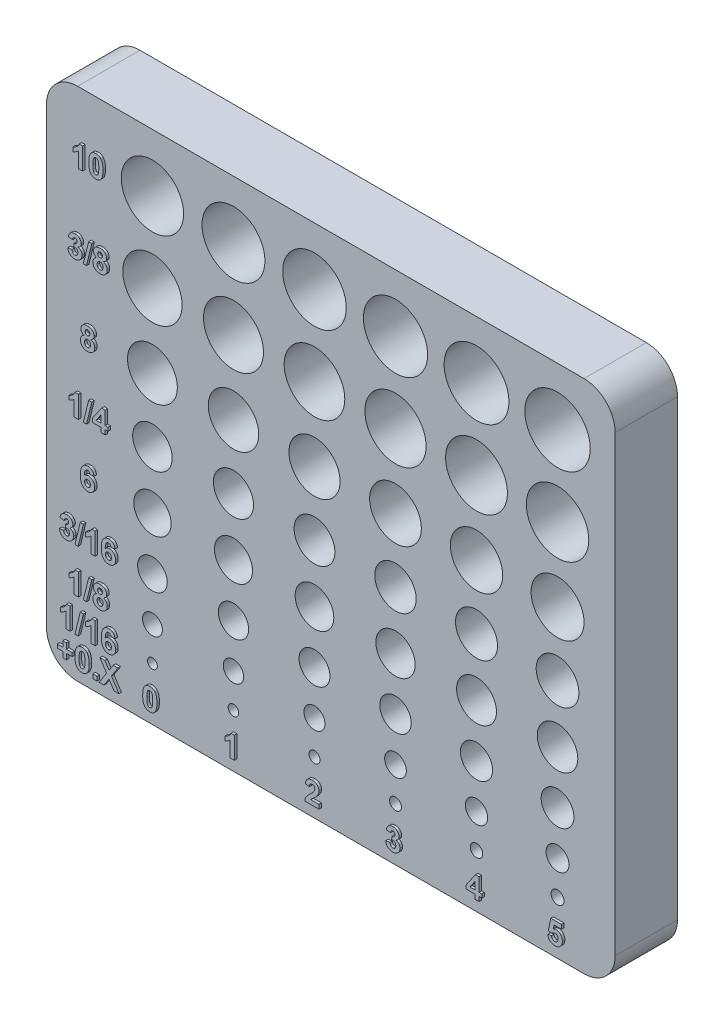
SolidWorks part; units mm, degrees
ref_plane "Front Plane" through (0, 0, 0) normal (0, 0, 1) x (1, 0, 0)
ref_plane "Top Plane" through (0, 0, 0) normal (0, 1, 0) x (1, 0, 0)
ref_plane "Right Plane" through (0, 0, 0) normal (1, 0, 0) x (0, 0, -1)
sketch "Sketch1" plane through (0, 0, 0) normal (0, 0, 1) x (1, 0, 0)
  line L0 (0, -3.52) -> (0, 3.52) construction
  line L1 (0, 64.9563) -> (0, 0) construction
  line L2 (13, 64.9563) -> (13, 0) construction
  line L3 (0, 0) -> (50000, 0) construction
  line L4 (0, 64.9563) -> (65, 64.9563) construction
  line L5 (26, 64.9563) -> (26, 0) construction
  line L6 (39, 64.9563) -> (39, 0) construction
  line L7 (52, 64.9563) -> (52, 0) construction
  line L8 (65, 64.9563) -> (65, 0) construction
  line L9 (0, 52.1438) -> (65, 52.1438) construction
  line L10 (0, 40.3312) -> (65, 40.3312) construction
  line L11 (0, 30.1062) -> (65, 30.1062) construction
  line L12 (0, 20.8812) -> (65, 20.8812) construction
  line L13 (0, 12.45) -> (65, 12.45) construction
  line L14 (0, 5.4312) -> (65, 5.4312) construction
  circle A0 centre (0, 0) radius 0.7938
  circle A1 centre (0, 5.4312) radius 1.5875
  circle A2 centre (0, 12.45) radius 2.3812
  circle A3 centre (0, 20.8812) radius 3
  circle A4 centre (0, 30.1062) radius 3.175
  circle A5 centre (0, 40.3312) radius 4
  circle A6 centre (0, 52.1438) radius 4.7625
  circle A7 centre (0, 64.9563) radius 5
  circle A8 centre (13, 0) radius 0.8438
  circle A9 centre (13, 5.4312) radius 1.6375
  circle A10 centre (13, 12.45) radius 2.4312
  circle A11 centre (13, 20.8812) radius 3.05
  circle A12 centre (13, 30.1062) radius 3.225
  circle A13 centre (13, 40.3312) radius 4.05
  circle A14 centre (13, 52.1438) radius 4.8125
  circle A15 centre (13, 64.9563) radius 5.05
  circle A16 centre (26, 0) radius 0.8937
  circle A17 centre (26, 5.4312) radius 1.6875
  circle A18 centre (26, 12.45) radius 2.4813
  circle A19 centre (26, 20.8812) radius 3.1
  circle A20 centre (26, 30.1062) radius 3.275
  circle A21 centre (26, 40.3312) radius 4.1
  circle A22 centre (26, 52.1438) radius 4.8625
  circle A23 centre (26, 64.9563) radius 5.1
  circle A24 centre (39, 0) radius 0.9437
  circle A25 centre (39, 5.4312) radius 1.7375
  circle A26 centre (39, 12.45) radius 2.5312
  circle A27 centre (39, 20.8812) radius 3.15
  circle A28 centre (39, 30.1062) radius 3.325
  circle A29 centre (39, 40.3312) radius 4.15
  circle A30 centre (39, 52.1438) radius 4.9125
  circle A31 centre (39, 64.9563) radius 5.15
  circle A32 centre (52, 0) radius 0.9938
  circle A33 centre (52, 5.4312) radius 1.7875
  circle A34 centre (52, 12.45) radius 2.5813
  circle A35 centre (52, 20.8812) radius 3.2
  circle A36 centre (52, 30.1062) radius 3.375
  circle A37 centre (52, 40.3312) radius 4.2
  circle A38 centre (52, 52.1438) radius 4.9625
  circle A39 centre (52, 64.9563) radius 5.2
  circle A40 centre (65, 0) radius 1.0437
  circle A41 centre (65, 5.4312) radius 1.8375
  circle A42 centre (65, 12.45) radius 2.6313
  circle A43 centre (65, 20.8812) radius 3.25
  circle A44 centre (65, 30.1062) radius 3.425
  circle A45 centre (65, 40.3312) radius 4.25
  circle A46 centre (65, 52.1438) radius 5.0125
  circle A47 centre (65, 64.9563) radius 5.25
  dimension "D1" = 1.5875
  dimension "D2" = 3.175
  dimension "D3" = 4.7625
  dimension "D4" = 6
  dimension "D5" = 6.35
  dimension "D6" = 8
  dimension "D7" = 9.525
  dimension "D8" = 10
  dimension "D16" = 1.6875
  dimension "D17" = 3.275
  dimension "D18" = 4.8625
  dimension "D19" = 6.1
  dimension "D20" = 6.45
  dimension "D21" = 8.1
  dimension "D22" = 9.625
  dimension "D23" = 10.1
  dimension "D32" = 1.7875
  dimension "D33" = 3.375
  dimension "D34" = 4.9625
  dimension "D35" = 6.2
  dimension "D36" = 6.55
  dimension "D37" = 8.2
  dimension "D38" = 9.725
  dimension "D39" = 10.2
  dimension "D48" = 1.8875
  dimension "D49" = 3.475
  dimension "D50" = 5.0625
  dimension "D51" = 6.3
  dimension "D52" = 6.65
  dimension "D53" = 8.3
  dimension "D54" = 9.825
  dimension "D55" = 10.3
  dimension "D64" = 1.9875
  dimension "D65" = 3.575
  dimension "D66" = 5.1625
  dimension "D67" = 6.4
  dimension "D68" = 6.75
  dimension "D69" = 8.4
  dimension "D70" = 9.925
  dimension "D71" = 10.4
  dimension "D80" = 2.0875
  dimension "D81" = 3.675
  dimension "D82" = 5.2625
  dimension "D83" = 6.5
  dimension "D84" = 6.85
  dimension "D85" = 8.5
  dimension "D86" = 10.025
  dimension "D87" = 10.5
  dimension "D9" = 3.05
  dimension "D10" = 3.05
  dimension "D11" = 3.05
  dimension "D12" = 3.05
  dimension "D13" = 3.05
  dimension "D14" = 3.05
  dimension "D15" = 3.05
  dimension "D31" = 13
  dimension "D47" = 13
  dimension "D63" = 13
  dimension "D79" = 13
  dimension "D95" = 13
  dimension "D24" = 2.55
  dimension "D25" = 2.55
sketch "Sketch2" plane through (0, 0, 0) normal (0, 0, 1) x (1, 0, 0)
  line L0 (-15, -1.75) -> (-5, -1.75) construction
  line L1 (-15, 3.6812) -> (-5, 3.6812) construction
  line L3 (-15, 10.7) -> (-5, 10.7) construction
  line L4 (-200000, 0) -> (250000, 0) construction
  line L5 (-15, 19.1312) -> (-5, 19.1312) construction
  line L6 (0, 64.9563) -> (65, 64.9563) construction
  line L7 (-15, 28.3562) -> (-5, 28.3562) construction
  line L8 (-5, 63.2063) -> (-15, 63.2063) construction
  line L9 (-15, 38.5812) -> (-5, 38.5812) construction
  line L10 (-5, 63.2063) -> (-5, 66.7063) construction
  line L11 (-5, 66.7063) -> (-15, 66.7063) construction
  line L12 (-15, 50.3938) -> (-5, 50.3938) construction
  line L13 (-15, 63.2063) -> (-5, 63.2063) construction
  line L14 (-15, 63.2063) -> (-5, 63.2063) construction
  line L15 (-10, 63.2063) -> (-10, -1.75) construction
  line L16 (-15, 63.2063) -> (-15, 50.3938) construction
  line L17 (-5, -1.75) -> (-15, -1.75) construction
  line L18 (-5, -1.75) -> (-5, 1.75) construction
  line L19 (-5, 1.75) -> (-15, 1.75) construction
  line L20 (-15, -1.75) -> (-15, 1.75) construction
  line L21 (-15, 50.3938) -> (-15, 38.5812) construction
  line L22 (-15, 38.5812) -> (-15, 28.3562) construction
  line L23 (-15, 28.3562) -> (-15, 19.1312) construction
  line L24 (-15, 19.1312) -> (-15, 10.7) construction
  line L25 (-15, 10.7) -> (-15, 3.6812) construction
  line L26 (-15, 3.6812) -> (-15, -1.75) construction
  line L27 (-15, 63.2063) -> (-15, 66.7063) construction
  line L28 (0, 64.9563) -> (0, 0) construction
  line L29 (-5, 3.6812) -> (-5, 7.1812) construction
  line L30 (-5, 10.7) -> (-5, 14.2) construction
  line L31 (-5, 19.1312) -> (-5, 22.6312) construction
  line L32 (-5, 28.3562) -> (-5, 31.8563) construction
  line L33 (-5, 38.5812) -> (-5, 42.0812) construction
  line L34 (-5, 50.3938) -> (-5, 53.8938) construction
  line L35 (0, 5.4312) -> (65, 5.4312) construction
  line L36 (0, 12.45) -> (65, 12.45) construction
  line L37 (0, 20.8812) -> (65, 20.8812) construction
  line L38 (0, 30.1062) -> (65, 30.1062) construction
  line L39 (0, 40.3312) -> (65, 40.3312) construction
  line L40 (0, 52.1438) -> (65, 52.1438) construction
  text T0 "<b>1/16</b>"
  text T2 "<b>8</b>"
  text T3 "<b>1/4</b>"
  text T4 "<b>6</b>"
  text T5 "<b>3/16</b>"
  text T6 "<b>3/8</b>"
  text T7 "<b>10</b>"
  text T8 "<b>1/8</b>"
  point P4 (-5, 5.4312)
  point P6 (-5, 64.9563)
  point P12 (-5, 0)
  point P43 (-5, 12.45)
  point P48 (-5, 20.8812)
  point P51 (-5, 30.1062)
  point P54 (-5, 40.3312)
  point P57 (-5, 52.1438)
  dimension "D2" = 3.5
  dimension "D1" = 10
  dimension "D3" = 10
sketch "Sketch3" plane through (0, 0, 0) normal (0, 0, 1) x (1, 0, 0)
  line L0 (-16, -6.5) -> (-4, -6.5) construction
  line L1 (-2.5, -6.5) -> (2.5, -6.5) construction
  line L2 (0, -42.2131) -> (0, 42.2131) construction
  line L3 (10.5, -6.5) -> (15.5, -6.5) construction
  line L4 (23.5, -6.5) -> (28.5, -6.5) construction
  line L5 (36.5, -6.5) -> (41.5, -6.5) construction
  line L6 (49.5, -6.5) -> (54.5, -6.5) construction
  line L7 (62.5, -6.5) -> (67.5, -6.5) construction
  line L8 (-10, 63.2063) -> (-10, -1.75) construction
  line L9 (-200000, 0) -> (250000, 0) construction
  text T0 "<b>0</b>"
  text T1 "<b>1</b>"
  text T2 "<b>2</b>"
  text T3 "<b>3</b>"
  text T4 "<b>4</b>"
  text T5 "<b>5</b>"
  text T6 "<b>+0.X</b>"
  point P4 (0, -6.5)
  point P7 (13, -6.5)
  point P21 (-10, -6.5)
  dimension "D2" = 13
  dimension "D3" = 5
  dimension "D4" = 6.5
  dimension "D5" = 12
  dimension "D1" = 6
sketch "Sketch4" plane through (0, 0, 0) normal (0, 0, 1) x (1, 0, 0)
  line L0 (-15, -1.75) -> (-15, 1.75) construction
  line L1 (-12, 74.2063) -> (69.25, 74.2063)
  line L2 (-17, 69.2063) -> (-17, -3.5)
  line L3 (-12, -8.5) -> (69.25, -8.5)
  line L4 (74.25, 69.2063) -> (74.25, -3.5)
  line L5 (62.5, -6.5) -> (67.5, -6.5) construction
  circle A0 centre (65, 64.9563) radius 5.25 construction
  arc A1 (-12, 74.2063) -> (-17, 69.2063) centre (-12, 69.2063) ccw
  arc A2 (69.25, 74.2063) -> (74.25, 69.2063) centre (69.25, 69.2063) cw
  arc A3 (69.25, -8.5) -> (74.25, -3.5) centre (69.25, -3.5) ccw
  arc A4 (-17, -3.5) -> (-12, -8.5) centre (-12, -3.5) ccw
  dimension "D2" = 4
  dimension "D3" = 4
  dimension "D5" = 5
  dimension "D1" = 2
  dimension "D4" = 2
extrude "Boss-Extrude1" add sketch "Sketch4" against normal blind 10
extrude "Cut-Extrude1" cut sketch "Sketch1" against normal through all
extrude "Boss-Extrude2" add sketch "Sketch2" along normal blind 0.4 separate body
extrude "Boss-Extrude3" add sketch "Sketch3" along normal up to surface (0.4 mm away) separate body up to face at (-6.5646, 0.2876, 0.4)
sketch "Sketch8" plane through (0, 0, 0) normal (0, 0, 1) x (1, 0, 0)
  line L0 (-16.2936, -2.5) -> (-6.2936, -2.5)
  line L1 (-16, -6.5) -> (-4, -6.5) construction
  point P2 (-11.2936, -2.5)
  dimension "D1" = 4
  dimension "D2" = 10
extrude "Extrude-Thin1" [suppressed] add sketch "Sketch8" along normal up to surface (0.4 mm away) thin
equation "\"inter\"= 3.05"
equation "\"D10@Sketch1\"=\"inter\""
equation "\"D11@Sketch1\"=\"inter\""
equation "\"D12@Sketch1\"=\"inter\""
equation "\"D13@Sketch1\"=\"inter\""
equation "\"D14@Sketch1\"=\"inter\""
equation "\"D15@Sketch1\"=\"inter\""
equation "\"D9@Sketch1\"=\"inter\""
equation "\"interX\"= 13"
equation "\"D31@Sketch1\"=\"interX\""
equation "\"D47@Sketch1\"=\"interX\""
equation "\"D63@Sketch1\"=\"interX\""
equation "\"D79@Sketch1\"=\"interX\""
equation "\"D95@Sketch1\"=\"interX\""
equation "\"D2@Sketch3\"=\"interX\""
